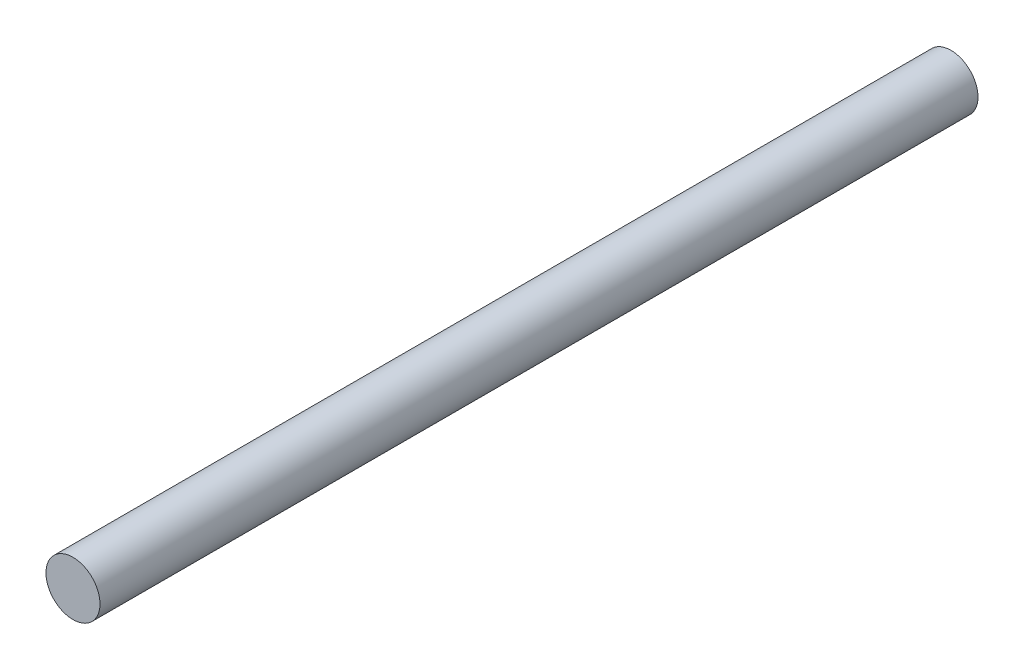
SolidWorks part; units mm, degrees
material "Acero inoxidable al cromo"
ref_plane "Alzado" through (0, 0, 0) normal (0, 0, 1) x (1, 0, 0)
ref_plane "Planta" through (0, 0, 0) normal (0, 1, 0) x (1, 0, 0)
ref_plane "Vista lateral" through (0, 0, 0) normal (1, 0, 0) x (0, 0, -1)
sketch "Croquis1" plane through (0, 0, 0) normal (0, 0, 1) x (1, 0, 0)
  circle A0 centre (0, 0) radius 4
  dimension "D1" = 8
extrude "Saliente-Extruir1" add sketch "Croquis1" along normal blind 130
